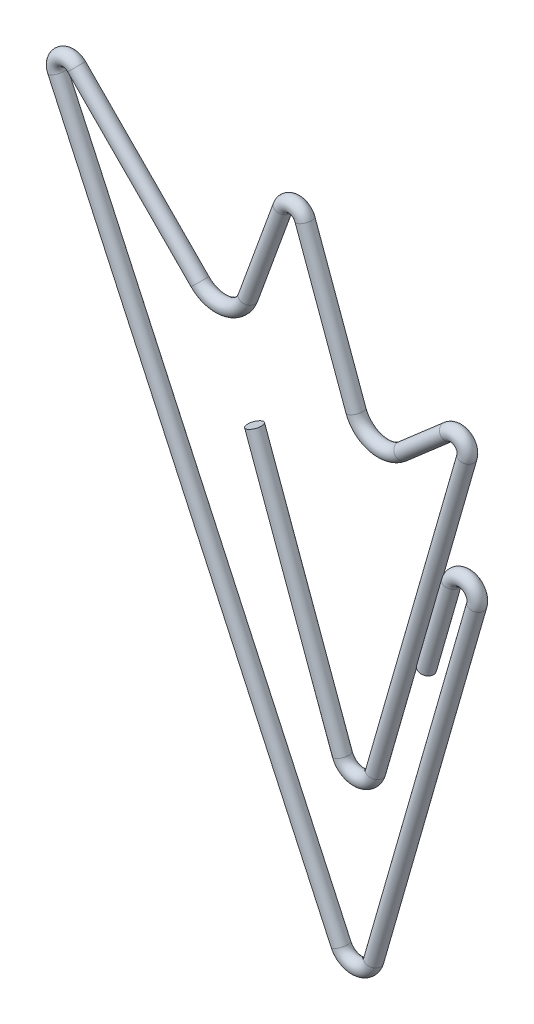
SolidWorks part; units mm, degrees
ref_plane "Спереди" through (0, 0, 0) normal (0, 0, 1) x (1, 0, 0)
ref_plane "Сверху" through (0, 0, 0) normal (0, 1, 0) x (1, 0, 0)
ref_plane "Справа" through (0, 0, 0) normal (1, 0, 0) x (0, 0, -1)
sketch "Эскиз1" plane through (0, 0, 0) normal (0, 0, 1) x (1, 0, 0)
  line L0 (0, 0) -> (18.1985, -50) construction
  line L1 (18.1985, -50) -> (38.2707, 20) construction
  line L2 (38.2707, 20) -> (19.8648, 4) construction
  line L3 (19.8648, 4) -> (6.7619, 40) construction
  line L4 (6.7619, 40) -> (-3.7933, 11) construction
  line L5 (-3.7933, 11) -> (-38.4752, 46) construction
  line L6 (-38.4752, 46) -> (18.1985, -77) construction
  line L7 (18.1985, -77) -> (38.0929, -7.6202) construction
  line L8 (33.7672, -6.3798) -> (29.466, -21.3798) construction
  line L9 (0, 0) -> (0, -30.4039) construction
  arc A0 (38.0929, -7.6202) -> (33.7672, -6.3798) centre (35.93, -7) ccw construction
  dimension "D15" = 70
  dimension "D1" = 20
  dimension "D2" = 50
  dimension "D3" = 16
  dimension "D4" = 70
  dimension "D5" = 16
  dimension "D6" = 33
  dimension "D7" = 40
  dimension "D8" = 20
  dimension "D9" = 123
  dimension "D10" = 35
  dimension "D11" = 29
  dimension "D12" = 77
  dimension "D13" = 4.5
  dimension "D14" = 15
sketch "Эскиз2" plane through (0, 0, 0) normal (0, 0, 1) x (1, 0, 0)
  line L0 (0, 0) -> (15.0406, -41.3238)
  line L1 (20.7435, -41.1246) -> (36.4096, 13.5097)
  line L2 (33.175, 15.5704) -> (25.3553, 8.7729)
  line L3 (38.2707, 20) -> (19.8648, 4) construction
  line L4 (17.3766, 10.8363) -> (8.6413, 34.8364)
  line L5 (4.8825, 34.8364) -> (-1.0954, 18.4124)
  line L6 (-9.3455, 16.6031) -> (-30.4914, 37.9431)
  line L7 (-33.7286, 35.6984) -> (14.8172, -69.6615)
  line L8 (20.4257, -69.233) -> (38.0929, -7.6202)
  line L9 (33.7672, -6.3798) -> (29.466, -21.3798)
  arc A0 (38.0929, -7.6202) -> (33.7672, -6.3798) centre (35.93, -7) ccw
  arc A1 (15.0406, -41.3238) -> (20.7435, -41.1246) centre (17.8597, -40.2977) ccw
  arc A2 (14.8172, -69.6615) -> (20.4257, -69.233) centre (17.5419, -68.4061) ccw
  arc A3 (36.4096, 13.5097) -> (33.175, 15.5704) centre (34.4871, 14.0609) ccw
  arc A4 (8.6413, 34.8364) -> (4.8825, 34.8364) centre (6.7619, 34.1524) ccw
  arc A5 (-30.4914, 37.9431) -> (-33.7286, 35.6984) centre (-31.9121, 36.5353) ccw
  arc A6 (25.3553, 8.7729) -> (17.3766, 10.8363) centre (22.075, 12.5464) cw
  arc A7 (-1.0954, 18.4124) -> (-9.3455, 16.6031) centre (-5.7938, 20.1225) cw
  point P27 (18.1985, -50)
  point P30 (18.1985, -77)
  point P33 (38.2707, 20)
  point P36 (6.7619, 40)
  point P39 (-38.4752, 46)
  point P42 (19.8648, 4)
  point P45 (-3.7933, 11)
  dimension "D1" = 3
  dimension "D2" = 2
  dimension "D3" = 5
ref_plane "Плоскость1" through (0, 0, 0) normal (0.342, -0.9397, 0) x (-0.9397, -0.342, 0)
sketch "Эскиз3" plane through (0, 0, 0) normal (0.342, -0.9397, 0) x (-0.9397, -0.342, 0)
  circle A0 centre (0, 0) radius 1.25
  dimension "D1" = 2.5
sweep "По траектории1" add profiles "Эскиз3" path "Эскиз2"
